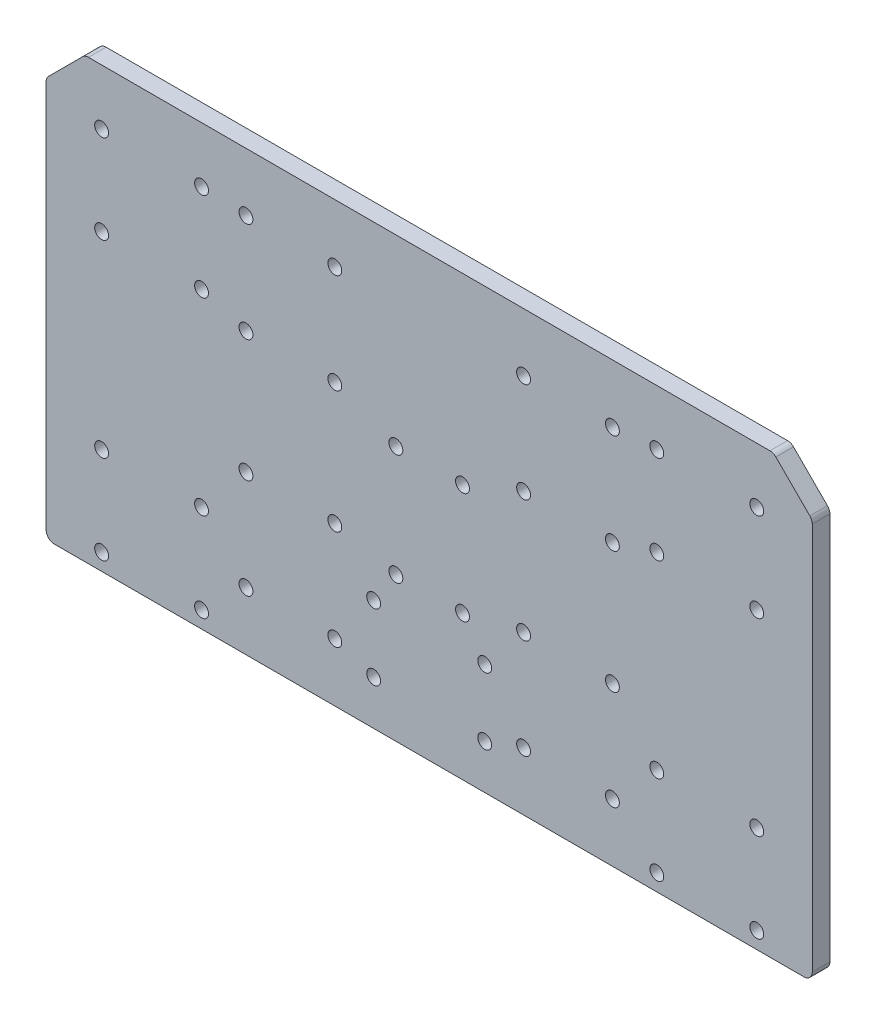
SolidWorks part; units mm, degrees
ref_plane "Front Plane" through (0, 0, 0) normal (0, 0, 1) x (1, 0, 0)
ref_plane "Top Plane" through (0, 0, 0) normal (0, 1, 0) x (1, 0, 0)
ref_plane "Right Plane" through (0, 0, 0) normal (1, 0, 0) x (0, 0, -1)
sketch "Sketch1" plane through (0, 0, 0) normal (0, 0, 1) x (1, 0, 0)
  line L0 (0, 0) -> (0, 72) construction
  line L1 (-138, 72) -> (138, 72)
  line L2 (-138, 72) -> (-138, -72)
  line L3 (-138, -72) -> (138, -72)
  line L4 (138, 72) -> (138, -72)
  line L5 (-138, 72) -> (138, -72) construction
  line L6 (-138, -72) -> (138, 72) construction
  line L7 (0, 72) -> (0, 0) construction
  line L8 (0, 0) -> (-138, 0) construction
  circle A0 centre (-118, -66) radius 2.5
  circle A1 centre (-82, -66) radius 2.5
  circle A2 centre (-82, -34) radius 2.5
  circle A3 centre (-118, -34) radius 2.5
  circle A4 centre (-118, 66) radius 2.5
  circle A5 centre (-82, 66) radius 2.5
  circle A6 centre (-82, 34) radius 2.5
  circle A7 centre (-118, 34) radius 2.5
  circle A8 centre (118, -66) radius 2.5
  circle A9 centre (82, -66) radius 2.5
  circle A10 centre (82, -34) radius 2.5
  circle A11 centre (118, -34) radius 2.5
  circle A12 centre (118, 34) radius 2.5
  circle A13 centre (82, 34) radius 2.5
  circle A14 centre (82, 66) radius 2.5
  circle A15 centre (118, 66) radius 2.5
  point P0 (0, 0)
  dimension "D5" = 5
  dimension "D6" = 5
  dimension "D7" = 5
  dimension "D8" = 5
  dimension "D9" = 100
  dimension "D10" = 200
  dimension "D1" = 144
  dimension "D2" = 276
  dimension "D3" = 36
  dimension "D4" = 32
extrude "Boss-Extrude1" add sketch "Sketch1" along normal blind 6.35
sketch "Sketch2" plane through (0, 0, 6.35) normal (0, 0, 1) x (1, 0, 0)
  line L0 (0, 72) -> (0, -72) construction
  line L1 (138, 72) -> (-138, 72) construction
  line L2 (-138, -72) -> (138, -72) construction
  line L3 (0, -72) -> (0, 0) construction
  circle A0 centre (-66, -15) radius 2.5
  circle A1 centre (-34, -15) radius 2.5
  circle A2 centre (-34, -51) radius 2.5
  circle A3 centre (-66, -51) radius 2.5
  circle A4 centre (66, -51) radius 2.5
  circle A5 centre (34, -51) radius 2.5
  circle A6 centre (34, -15) radius 2.5
  circle A7 centre (66, -15) radius 2.5
  dimension "D1" = 5
  dimension "D2" = 5
  dimension "D3" = 32
  dimension "D4" = 36
  dimension "D5" = 100
  dimension "D7" = 5
  dimension "D8" = 5
  dimension "D6" = 21
extrude "Cut-Extrude1" cut sketch "Sketch2" against normal through all
sketch "Sketch3" plane through (0, 0, 6.35) normal (0, 0, 1) x (1, 0, 0)
  line L0 (-138, 72) -> (-124, 86)
  line L1 (-124, 86) -> (124, 86)
  line L2 (124, 86) -> (138, 72)
  line L3 (138, 72) -> (-138, 72)
  dimension "D1" = 14
  dimension "D2" = 14
  dimension "D3" = 14
extrude "Boss-Extrude2" add sketch "Sketch3" against normal through all
sketch "Sketch4" plane through (0, 0, 6.35) normal (0, 0, 1) x (1, 0, 0)
  line L0 (0, 0) -> (0, 86) construction
  line L1 (124, 86) -> (-124, 86) construction
  circle A0 centre (-66, -15) radius 2.5
  circle A1 centre (-34, -15) radius 2.5
  circle A2 centre (-34, -51) radius 2.5
  circle A3 centre (-66, -51) radius 2.5
  circle A4 centre (-66, 29) radius 2.5
  circle A5 centre (-66, 65) radius 2.5
  circle A6 centre (-34, 65) radius 2.5
  circle A7 centre (-34, 29) radius 2.5
  circle A8 centre (34, 29) radius 2.5
  circle A9 centre (34, 65) radius 2.5
  circle A10 centre (66, 65) radius 2.5
  circle A11 centre (66, 29) radius 2.5
  circle A12 centre (34, -51) radius 2.5
  circle A13 centre (34, -15) radius 2.5
  circle A14 centre (66, -15) radius 2.5
  circle A15 centre (66, -51) radius 2.5
  dimension "D3" = 5
  dimension "D4" = 5
  dimension "D5" = 5
  dimension "D6" = 5
  dimension "D2" = 44
  dimension "D1" = 2
extrude "Cut-Extrude2" cut sketch "Sketch4" against normal through all
fillet "Fillet1" radius 3 6 edges at (124, 86, 3.175) (-124, 86, 3.175) (-138, 72, 3.175) (-138, -72, 3.175) (138, -72, 3.175) (138, 72, 3.175)
sketch "Sketch5" plane through (0, 0, 6.35) normal (0, 0, 1) x (1, 0, 0)
  line L0 (-135, -72) -> (135, -72) construction
  line L1 (34, -15) -> (34, 29) construction
  line L3 (-34, -15) -> (-34, 29) construction
  line L4 (0, -44) -> (0, 104.5319) construction
  line L5 (0, 104.5319) -> (0, -44) construction
  line L6 (0, -44) -> (-66.1694, -44) construction
  circle A0 centre (-20, -32) radius 2.5
  circle A1 centre (20, -32) radius 2.5
  circle A2 centre (20, -56) radius 2.5
  circle A3 centre (-20, -56) radius 2.5
  dimension "D3" = 5
  dimension "D1" = 20
  dimension "D2" = 12
  dimension "D4" = 28
extrude "Cut-Extrude3" cut sketch "Sketch5" against normal through all
sketch "Sketch6" plane through (0, 0, 6.35) normal (0, 0, 1) x (1, 0, 0)
  line L0 (0, 0) -> (0, 52.8671) construction
  line L1 (0, 52.8671) -> (0, 0) construction
  line L2 (0, 0) -> (88.0618, 0) construction
  circle A0 centre (12, 20) radius 2.5
  circle A1 centre (12, -20) radius 2.5
  circle A2 centre (-12, -20) radius 2.5
  circle A3 centre (-12, 20) radius 2.5
  dimension "D1" = 20
  dimension "D2" = 12
  dimension "D3" = 5
extrude "Cut-Extrude4" cut sketch "Sketch6" against normal through all
